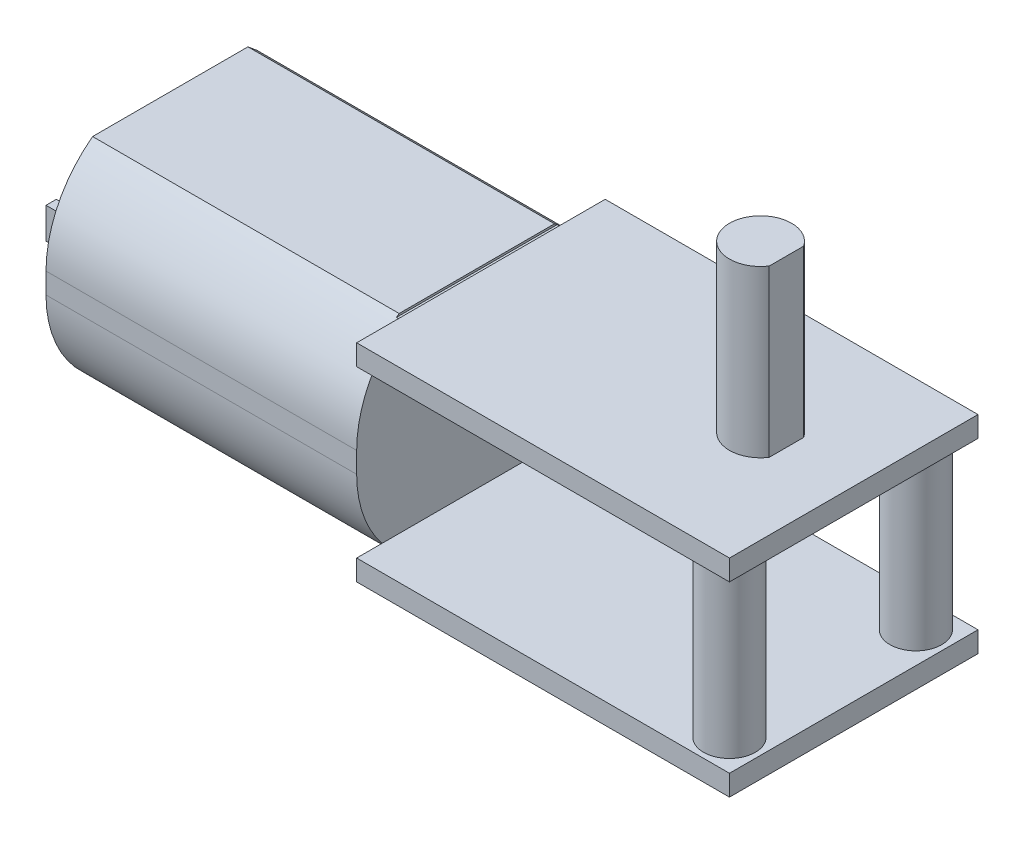
SolidWorks part; units mm, degrees
ref_plane "Front Plane" through (0, 0, 0) normal (0, 0, 1) x (1, 0, 0)
ref_plane "Top Plane" through (0, 0, 0) normal (0, 1, 0) x (1, 0, 0)
ref_plane "Right Plane" through (0, 0, 0) normal (1, 0, 0) x (0, 0, -1)
sketch "Sketch1" plane through (0, 0, 0) normal (0, 1, 0) x (1, 0, 0)
  line L1 (-9, -6) -> (9, -6)
  line L2 (-9, -6) -> (-9, 6)
  line L3 (-9, 6) -> (9, 6)
  line L4 (9, -6) -> (9, 6)
  point P4 (0, 6)
  point P6 (9, 0)
  dimension "D1" = 12
  dimension "D2" = 18
extrude "Boss-Extrude1" add sketch "Sketch1" along normal blind 1
sketch "Sketch2" plane through (0, 1, 0) normal (0, 1, 0) x (1, 0, 0)
  line L0 (9, -6) -> (9, 6) construction
  line L1 (9, 6) -> (-9, 6) construction
  line L2 (0, 0) -> (9, 0) construction
  circle A0 centre (7.5, 4.5) radius 1.25
  circle A1 centre (7.5, -4.5) radius 1.25
  dimension "D1" = 2.5
  dimension "D2" = 1.5
  dimension "D3" = 1.5
extrude "Boss-Extrude2" add sketch "Sketch2" along normal blind 8
sketch "Sketch3" plane through (0, 9, 0) normal (0, 1, 0) x (1, 0, 0)
  line L4 (-9, 6) -> (-9, -6)
  line L5 (9, 6) -> (-9, 6)
  line L6 (9, -6) -> (9, 6)
  line L7 (-9, -6) -> (9, -6)
  line L8 (-9, 6) -> (-9, -6)
  line L9 (9, 6) -> (-9, 6)
  line L10 (9, -6) -> (9, 6)
  line L11 (-9, -6) -> (9, -6)
  dimension "D1" = 0
extrude "Boss-Extrude3" add sketch "Sketch3" along normal blind 1
sketch "Sketch4" plane through (-9, 0, 0) normal (-1, 0, 0) x (0, 0, 1)
  line L0 (-6, 5) -> (6, 5) construction
  line L1 (-6, 10) -> (6, 10) construction
  line L2 (-6, 10) -> (-6, 0) construction
  line L3 (-6, 0) -> (6, 0) construction
  line L4 (6, 10) -> (6, 0) construction
  line L5 (0, 5) -> (0, 10) construction
  line L6 (-3.75, 0) -> (3.75, 0)
  line L7 (-3.75, 10) -> (3.75, 10)
  line L8 (-6, 5.5) -> (-6, 4.5)
  line L9 (6, 5.5) -> (6, 4.5)
  arc A0 (3.75, 10) -> (6, 5.5) centre (0.375, 5.5) cw
  arc A1 (-3.75, 10) -> (-6, 5.5) centre (-0.375, 5.5) ccw
  arc A2 (3.75, 0) -> (6, 4.5) centre (0.375, 4.5) ccw
  arc A3 (-3.75, 0) -> (-6, 4.5) centre (-0.375, 4.5) cw
  dimension "D1" = 0.5
  dimension "D2" = 3.75
extrude "Boss-Extrude4" add sketch "Sketch4" along normal blind 15
sketch "Sketch5" plane through (-24, 0, 0) normal (-1, 0, 0) x (0, 0, 1)
  line L0 (-6, 5.5) -> (-6, 4.5) construction
  circle A0 centre (0, 5) radius 2.5
  circle A1 centre (0, 5) radius 0.5
  point P7 (-6, 5)
  dimension "D1" = 5
  dimension "D2" = 1
extrude "Boss-Extrude5" add sketch "Sketch5" along normal blind 1
sketch "Sketch6" plane through (-24, 0, 0) normal (-1, 0, 0) x (0, 0, 1)
  line L0 (0, 5) -> (0, 0) construction
  line L1 (-3.5, 5.75) -> (-3, 5.75)
  line L2 (-3.5, 5.75) -> (-3.5, 4.25)
  line L3 (-3.5, 4.25) -> (-3, 4.25)
  line L4 (-3, 5.75) -> (-3, 4.25)
  line L5 (3.5, 4.25) -> (3, 4.25)
  line L6 (3, 5.75) -> (3, 4.25)
  line L7 (3.5, 5.75) -> (3, 5.75)
  line L8 (3.5, 5.75) -> (3.5, 4.25)
  point P8 (0, 0)
  point P9 (-3, 5)
  dimension "D1" = 3
  dimension "D2" = 0.5
  dimension "D3" = 1.5
extrude "Boss-Extrude6" add sketch "Sketch6" along normal blind 2.5
sketch "Sketch7" plane through (0, 10, 0) normal (0, 1, 0) x (1, 0, 0)
  line L0 (5.75, 0.8292) -> (5.75, -0.8292)
  line L1 (9, -6) -> (9, 6) construction
  circle A0 centre (4.5, 0) radius 1.5
  dimension "D1" = 4.5
  dimension "3" = 3
  dimension "D2" = 1.25
extrude "Boss-Extrude7" add sketch "Sketch7" along normal blind 8 contours L0 A0
sketch "Sketch8" plane through (0, 0, 6) normal (0, 0, 1) x (1, 0, 0)
  line L0 (-24, 5) -> (0, 5) construction
  line L1 (-9, 10) -> (-9.2, 10)
  line L2 (-9, 10) -> (-9, 9.9)
  line L3 (-9, 9.9) -> (-9.2, 9.9)
  line L4 (-9.2, 10) -> (-9.2, 9.9)
  line L5 (-24, 4.5) -> (-24, 5.5) construction
  line L6 (-9, 0.1) -> (-9.2, 0.1)
  line L7 (-9.2, 0) -> (-9.2, 0.1)
  line L8 (-9, 0) -> (-9.2, 0)
  line L9 (-9, 0) -> (-9, 0.1)
  dimension "D1" = 0.1
  dimension "D2" = 0.2
extrude "Cut-Extrude1" cut sketch "Sketch8" against normal through all
